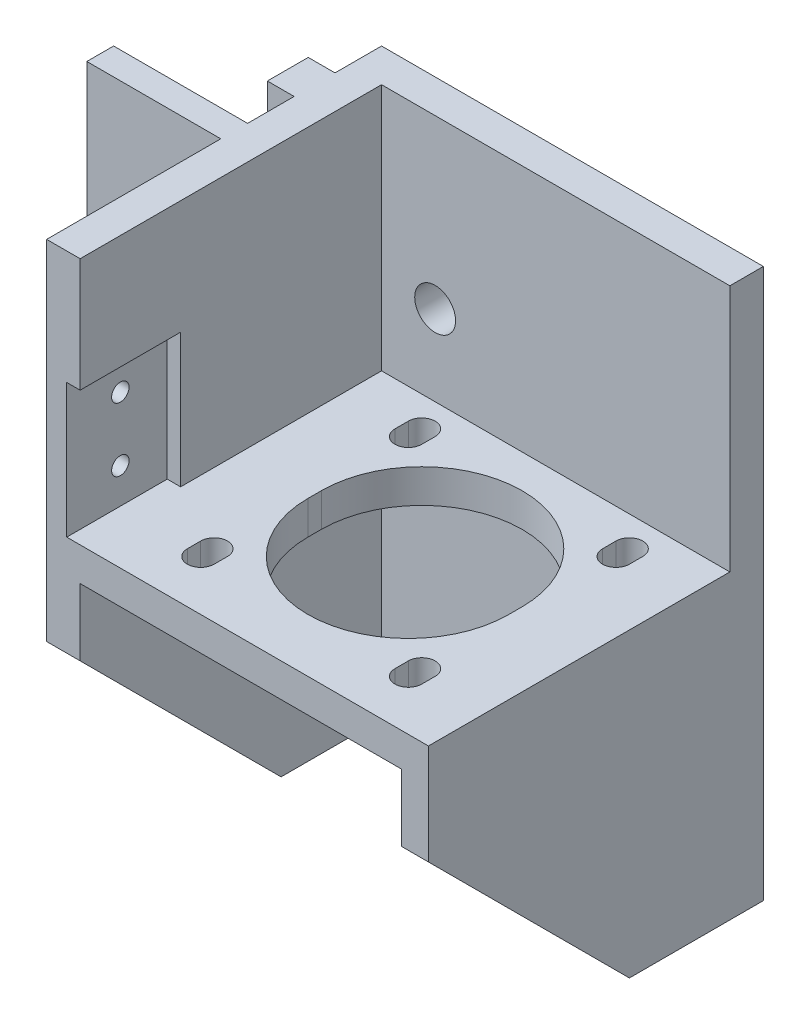
SolidWorks part; units mm, degrees
ref_plane "前视基准面" through (0, 0, 0) normal (0, 0, 1) x (1, 0, 0)
ref_plane "上视基准面" through (0, 0, 0) normal (0, 1, 0) x (1, 0, 0)
ref_plane "右视基准面" through (0, 0, 0) normal (1, 0, 0) x (0, 0, -1)
other "Configuration Table"
sketch "草图1" plane through (0, 0, 0) normal (0, 1, 0) x (1, 0, 0)
  line L6 (-28.5, -25) -> (28.5, -25)
  line L7 (-28.5, -25) -> (-28.5, 25)
  line L8 (-28.5, 25) -> (28.5, 25)
  line L9 (28.5, -25) -> (28.5, 25)
extrude "凸台-拉伸1" add sketch "草图1" along normal blind 5 contours L7 L6 L9 L8
sketch "草图2" plane through (0, 5, 0) normal (0, 1, 0) x (1, 0, 0)
  line L0 (-28.5, 25) -> (28.5, 25) construction
  line L1 (-28.5, -25) -> (-23.5, -25)
  line L2 (-28.5, -25) -> (-28.5, 25)
  line L3 (-28.5, 25) -> (-23.5, 25)
  line L4 (-23.5, -25) -> (-23.5, 25)
  line L6 (28.5, 25) -> (-28.5, 25)
  line L7 (28.5, 25) -> (28.5, 20)
  line L8 (28.5, 20) -> (-28.5, 20)
  line L9 (-28.5, 25) -> (-28.5, 20)
  line M9 (28.5, 25) -> (-28.5, 25)
  line M12 (28.5, -25) -> (28.5, 25)
extrude "凸台-拉伸3" add sketch "草图2" along normal blind 30 contours L8 L4 M12 M9
sketch "草图3" plane through (0, 0, 0) normal (0, -1, 0) x (1, 0, 0)
  line L0 (-28.5, 25) -> (28.5, 25) construction
  line L1 (-28.5, -25) -> (-23.5, -25)
  line L2 (-28.5, -25) -> (-28.5, 25)
  line L3 (-28.5, 25) -> (-23.5, 25)
  line L4 (-23.5, -25) -> (-23.5, 25)
  line L5 (28.5, 25) -> (28.5, -25) construction
  line L6 (-28.5, -25) -> (28.5, -25)
  line L7 (-28.5, -25) -> (-28.5, -20)
  line L8 (-28.5, -20) -> (28.5, -20)
  line L9 (28.5, -25) -> (28.5, -20)
  line L11 (28.5, 25) -> (24.5, 25)
  line L12 (28.5, 25) -> (28.5, -25)
  line L13 (28.5, -25) -> (24.5, -25)
  line L14 (24.5, 25) -> (24.5, -25)
  line M10 (-28.5, -25) -> (28.5, -25)
  line M11 (28.5, -25) -> (28.5, 25)
  line M12 (28.5, 25) -> (-28.5, 25)
extrude "凸台-拉伸4" add sketch "草图3" along normal blind 40 contours L14 L8 M12 M11 | L14 L8 L4 M10 | L8 L14 L6 M11
sketch "草图5" plane through (28.5, 0, 0) normal (1, 0, 0) x (0, 0, -1)
  line L1 (25, -40) -> (-25, -40) construction
  line L3 (-25, 5) -> (-25, -40) construction
  line L4 (-25, -10) -> (5, -40)
  line L5 (-25, -10) -> (-25, -40)
  line L6 (-25, -40) -> (5, -40)
extrude "切除-拉伸1" cut sketch "草图5" against normal blind 80 contours L4 L6 L5
sketch "草图6" plane through (0, 5, 0) normal (0, 1, 0) x (1, 0, 0)
  line L0 (20.5, -17) -> (20.5, -19)
  line L1 (-23.5, -25) -> (28.5, -25) construction
  line L4 (28.5, 20) -> (-23.5, 20) construction
  line L5 (16.5, -17) -> (16.5, -19)
  line L9 (2.5, -25) -> (2.5, 20)
  line L11 (-15.5, -19) -> (-15.5, -17)
  line L14 (-11.5, -17) -> (-11.5, -19)
  line L15 (16.5, 13) -> (16.5, 11)
  line L16 (-11.5, 13) -> (-11.5, 11)
  line L17 (-15.5, 13) -> (-15.5, 11)
  line L18 (20.5, 13) -> (20.5, 11)
  arc A2 (16.5, -17) -> (20.5, -17) centre (18.5, -17) cw
  arc A3 (16.5, -19) -> (20.5, -19) centre (18.5, -19) ccw
  arc A4 (-15.5, -17) -> (-11.5, -17) centre (-13.5, -17) cw
  arc A5 (-15.5, -19) -> (-11.5, -19) centre (-13.5, -19) ccw
  circle A6 centre (2.5, -1) radius 15
  arc A7 (-15.5, 11) -> (-11.5, 11) centre (-13.5, 11) ccw
  arc A8 (-15.5, 13) -> (-11.5, 13) centre (-13.5, 13) cw
  arc A9 (16.5, 11) -> (20.5, 11) centre (18.5, 11) ccw
  arc A10 (16.5, 13) -> (20.5, 13) centre (18.5, 13) cw
extrude "切除-拉伸2" cut sketch "草图6" against normal blind 80 contours L9 A6 | L9 A6 | A8 L17 A7 L16 | L11 A5 L14 A4 | L5 A3 L0 A2 | A10 L15 A9 L18
sketch "草图7" plane through (0, 0, -20) normal (0, 0, 1) x (1, 0, 0)
  line L0 (-23.5, 5) -> (-11.5, 5)
  line L1 (28.5, 5) -> (-23.5, 5) construction
  line L2 (-11.5, 5) -> (-11.5, 21)
  line L3 (-11.5, 21) -> (-15.5, 21)
  line L4 (-15.5, 21) -> (-15.5, 17)
  circle A4 centre (-15.5, 17) radius 3
extrude "切除-拉伸6" cut sketch "草图7" against normal blind 80 contours A4
sketch "草图8" plane through (-28.5, 0, 0) normal (-1, 0, 0) x (0, 0, 1)
  line L0 (-18.05, 35) -> (-11.95, 35)
  line L1 (25, 35) -> (-25, 35) construction
  line L2 (-5, 35) -> (-5, 15)
  line L3 (-18.05, -40) -> (-11.95, -40)
  line L7 (-25, -40) -> (-5, -40) construction
  line L8 (-18.05, -40) -> (-18.05, 35)
  line L10 (-11.95, 35) -> (-11.95, -40)
extrude "凸台-拉伸5" add sketch "草图8" along normal blind 4 contours L3 L10 L0 L8
sketch "草图9" plane through (-28.5, 0, 0) normal (-1, 0, 0) x (0, 0, 1)
  line L0 (-5, -40) -> (-5, 35)
  line L2 (25, 35) -> (-11.95, 35) construction
  line L3 (-5, 35) -> (-1, 35)
  line L4 (-1, 35) -> (-1, -36)
  line L5 (-5, -40) -> (25, -10) construction
  line L6 (-1, -36) -> (-5, -40)
extrude "凸台-拉伸6" add sketch "草图9" along normal blind 20 contours L6 L0 L3 L4
sketch "草图10" plane through (0, 0, -1) normal (0, 0, 1) x (1, 0, 0)
  line L1 (-48.5, 35) -> (-48.5, -36) construction
  line L2 (-48.5, 5) -> (-48.5, 0)
  line L3 (-48.5, 0) -> (-28.5, 0)
  line L4 (-28.5, 35) -> (-28.5, -10) construction
  line L5 (-28.5, 0) -> (-28.5, 5)
  line L6 (-28.5, 5) -> (-48.5, 5)
extrude "凸台-拉伸7" add sketch "草图10" along normal blind 26 contours L2 L3 L5 L6
sketch "草图11" plane through (0, 0, 0) normal (0, -1, 0) x (1, 0, 0)
  line L0 (-48.5, 25) -> (-48.5, -1)
  line L1 (-48.5, -1) -> (-28.5, 25)
  line L2 (-28.5, 25) -> (-48.5, 25)
extrude "切除-拉伸7" cut sketch "草图11" against normal blind 26 contours L2 L0 L1
sketch "草图14" plane through (0, 35, 0) normal (0, 1, 0) x (1, 0, 0)
  line L1 (-28.5, 25) -> (28.5, 25)
  line L2 (-28.5, 25) -> (-28.5, 20)
  line L3 (-28.5, 20) -> (28.5, 20)
  line L4 (28.5, 25) -> (28.5, 20)
  line L5 (-23.5, -25) -> (-28.5, -25)
  line L6 (-23.5, -25) -> (-23.5, 20)
  line L7 (-23.5, 20) -> (-28.5, 20)
  line L8 (-28.5, -25) -> (-28.5, 20)
  line L9 (-48.5, 5) -> (-28.5, 5)
  line L10 (-48.5, 5) -> (-48.5, 1)
  line L11 (-48.5, 1) -> (-28.5, 1)
  line L12 (-28.5, 5) -> (-28.5, 1)
  line L13 (-32.5, 11.95) -> (-28.5, 11.95)
  line L14 (-32.5, 11.95) -> (-32.5, 18.05)
  line L15 (-32.5, 18.05) -> (-28.5, 18.05)
  line L16 (-28.5, 11.95) -> (-28.5, 18.05)
  line M8 (-28.5, 25) -> (-28.5, 18.05)
  line M9 (-28.5, 18.05) -> (-32.5, 18.05)
  line M10 (-32.5, 18.05) -> (-32.5, 11.95)
  line M11 (-32.5, 11.95) -> (-28.5, 11.95)
  line M12 (-28.5, 11.95) -> (-28.5, 5)
  line M13 (-28.5, 5) -> (-48.5, 5)
  line M14 (-48.5, 5) -> (-48.5, 1)
  line M15 (-48.5, 1) -> (-28.5, 1)
  line M16 (-28.5, 1) -> (-28.5, -25)
  line M17 (-28.5, -25) -> (-23.5, -25)
  line M18 (-23.5, -25) -> (-23.5, 20)
extrude "凸台-拉伸8" add sketch "草图14" along normal blind 7 contours L8 L3 M16 M17 M18 M8 M12 | L8 M11 M9 M10 | L8 M15 M13 M14
sketch "草图15" plane through (0, 0, -1) normal (0, 0, 1) x (1, 0, 0)
  line L0 (-48.5, 42) -> (-28.5, 5)
  line L1 (-48.5, 0) -> (-28.5, -36)
  circle A0 centre (-38.5, 23.5) radius 2.55
  circle A1 centre (-38.5, -18) radius 2.55
extrude "切除-拉伸9" cut sketch "草图15" against normal blind 7 contours L0 A0 | L0 A0 | L1 A1 | L1 A1
sketch "草图16" plane through (0, 5, 0) normal (0, 1, 0) x (1, 0, 0)
  line L1 (-16.5233, 16.4764) -> (-10.9881, 16.4764)
  line L2 (-16.5233, 16.4764) -> (-16.5233, 8.6568)
  line L3 (-16.5233, 8.6568) -> (-10.9881, 8.6568)
  line L4 (-10.9881, 16.4764) -> (-10.9881, 8.6568)
  line L5 (-16.9626, -13.44) -> (-10.9881, -13.44)
  line L6 (-16.9626, -13.44) -> (-16.9626, -21.5671)
  line L7 (-16.9626, -21.5671) -> (-10.9881, -21.5671)
  line L8 (-10.9881, -13.44) -> (-10.9881, -21.5671)
  line L9 (15.0625, -13.44) -> (22.7063, -13.44)
  line L10 (15.0625, -13.44) -> (15.0625, -21.9625)
  line L11 (15.0625, -21.9625) -> (22.7063, -21.9625)
  line L12 (22.7063, -13.44) -> (22.7063, -21.9625)
  line L13 (15.0625, 16.74) -> (22.4428, 16.74)
  line L14 (15.0625, 16.74) -> (15.0625, 8.6568)
  line L15 (15.0625, 8.6568) -> (22.4428, 8.6568)
  line L16 (22.4428, 16.74) -> (22.4428, 8.6568)
extrude "凸台-拉伸9" add sketch "草图16" against normal blind 5
sketch "草图17" plane through (0, 5, 0) normal (0, 1, 0) x (1, 0, 0)
  line L6 (-15, 15.5) -> (-15, 13.5)
  line L16 (16, -15.5) -> (16, -17.5)
  line L17 (-11, 15.5) -> (-11, 13.5)
  line L18 (16, 15.5) -> (16, 13.5)
  line L21 (20, 15.5) -> (20, 13.5)
  line L22 (-11, -15.5) -> (-11, -17.5)
  line L23 (20, -15.5) -> (20, -17.5)
  line L25 (-15, -15.5) -> (-15, -17.5)
  arc A9 (-15, 15.5) -> (-11, 15.5) centre (-13, 15.5) cw
  arc A10 (-15, 13.5) -> (-11, 13.5) centre (-13, 13.5) ccw
  arc A11 (16, 15.5) -> (20, 15.5) centre (18, 15.5) cw
  arc A12 (16, 13.5) -> (20, 13.5) centre (18, 13.5) ccw
  arc A13 (20, -15.5) -> (16, -15.5) centre (18, -15.5) ccw
  arc A14 (20, -17.5) -> (16, -17.5) centre (18, -17.5) cw
  arc A15 (-11, -15.5) -> (-15, -15.5) centre (-13, -15.5) ccw
  arc A16 (-11, -17.5) -> (-15, -17.5) centre (-13, -17.5) cw
extrude "切除-拉伸10" cut sketch "草图17" against normal blind 5
sketch "草图18" plane through (0, 5, 0) normal (0, 1, 0) x (1, 0, 0)
  line L3 (-12.5, -1) -> (-12.5, 0)
  line L4 (-12.5, -1) -> (-12.5, -2)
  line L5 (17.5, -1) -> (17.5, 0)
  line L6 (17.5, -1) -> (17.5, -2)
  circle A1 centre (2.5, -1) radius 15 construction
  arc A2 (-12.5, 0) -> (17.5, 0) centre (2.5, 0) cw
  arc A3 (-12.5, -2) -> (17.5, -2) centre (2.5, -2) ccw
extrude "切除-拉伸11" cut sketch "草图18" against normal blind 5
sketch "草图19" plane through (0, 0, -25) normal (0, 0, -1) x (-1, 0, 0)
  circle A0 centre (15.5, 17) radius 3.05
extrude "切除-拉伸12" cut sketch "草图19" against normal blind 10
sketch "草图20" plane through (0, 5, 0) normal (0, 1, 0) x (1, 0, 0)
  line L4 (-15, 13.5) -> (-15, 15.5)
  line L6 (-11, 15.5) -> (-11, 13.5)
  arc A2 (-11, 13.5) -> (-15, 13.5) centre (-13, 13.5) cw
  arc A3 (-15, 15.5) -> (-11, 15.5) centre (-13, 15.5) cw
extrude "切除-拉伸13" cut sketch "草图20" against normal blind 10 contours A2 L4 A3 L6
sketch "草图22" plane through (0, 0, 25) normal (0, 0, 1) x (1, 0, 0)
  line L1 (-23.5, 5) -> (-25.5, 5)
  line L2 (-23.5, 5) -> (-23.5, 25)
  line L3 (-23.5, 25) -> (-25.5, 25)
  line L4 (-25.5, 5) -> (-25.5, 25)
  line M15 (-23.5, 5) -> (-23.5, 42)
extrude "切除-拉伸14" cut sketch "草图22" against normal blind 15 contours L4 L1 L3 M15
sketch "草图23" plane through (-25.5, 0, 0) normal (1, 0, 0) x (0, 0, -1)
  line L0 (-25, 25) -> (-25, 5)
  line L1 (-25, 15) -> (-17, 15)
  line L2 (-17, 15) -> (-17, 19.75)
  line L4 (-17, 15) -> (-17, 10.25)
  circle A0 centre (-17, 19.75) radius 1.3
  circle A1 centre (-17, 10.25) radius 1.3
extrude "切除-拉伸15" cut sketch "草图23" against normal blind 15
